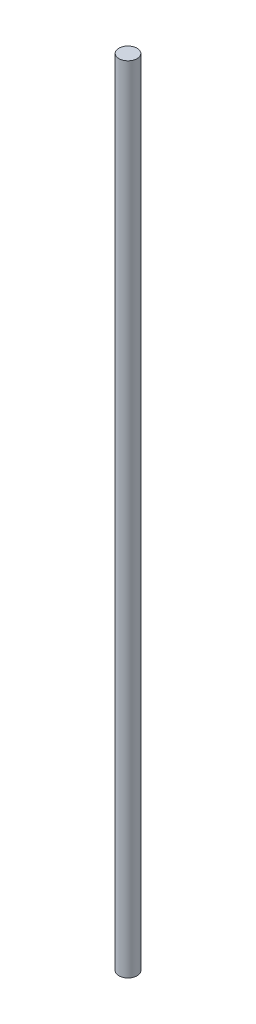
SolidWorks part; units mm, degrees
material "AISI 316 Annealed Stainless Steel Bar (SS)"
ref_plane "Front Plane" through (0, 0, 0) normal (0, 0, 1) x (1, 0, 0)
ref_plane "Top Plane" through (0, 0, 0) normal (0, 1, 0) x (1, 0, 0)
ref_plane "Right Plane" through (0, 0, 0) normal (1, 0, 0) x (0, 0, -1)
sketch "Sketch1" plane through (0, 0, 0) normal (0, 1, 0) x (1, 0, 0)
  circle A0 centre (0, 0) radius 4
  dimension "D1" = 8
extrude "Boss-Extrude1" add sketch "Sketch1" against normal blind 350
equation "\"rod_diameter\"= 8"
equation "\"rod_hole_thickness\"= 4"
equation "\"rod_radius\"= \"rod_diameter\" / 2"
equation "\"platter_diameter\"= 320"
equation "\"platter_radius\"= \"platter_diameter\" / 2"
equation "\"extruder_mount_hole_spacing\"= 75"
equation "\"arm_rod_spacing\"= 40"
equation "\"top_frame_rod_spacing\"= \"arm_rod_spacing\" + 40"
equation "\"motor_level_rod_spacing\"= 15"
equation "\"linear_bearing_diameter\"= 15"
equation "\"z_rod_spacing\"= 75"
equation "\"platter_rod_spacing\"= 50"
equation "\"rod_nut_thickness\"= 6.5"
equation "\"rod_nut_inscribed_diameter\"= 13"
equation "\"z_height\"= 350"
equation "\"D1@Sketch1\"= \"rod_diameter\""
equation "\"D1@Boss-Extrude1\"= \"z_height\""
